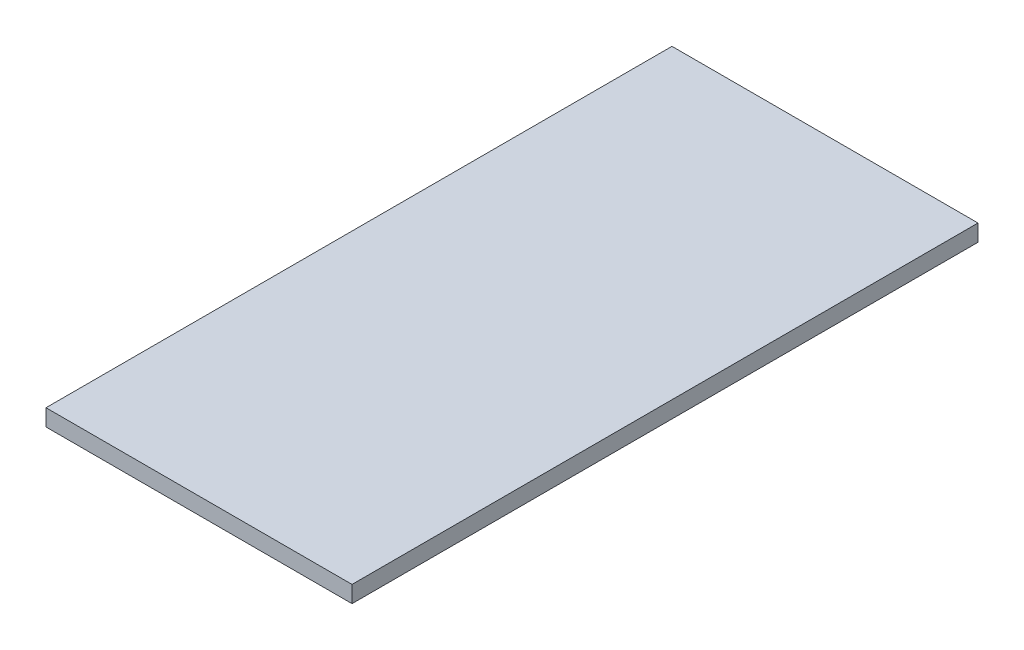
SolidWorks part; units mm, degrees
ref_plane "Front Plane" through (0, 0, 0) normal (0, 0, 1) x (1, 0, 0)
ref_plane "Top Plane" through (0, 0, 0) normal (0, 1, 0) x (1, 0, 0)
ref_plane "Right Plane" through (0, 0, 0) normal (1, 0, 0) x (0, 0, -1)
sketch "Sketch1" plane through (0, 0, 0) normal (0, 1, 0) x (1, 0, 0)
  line L1 (-11, 22.5) -> (11, 22.5)
  line L2 (-11, 22.5) -> (-11, -22.5)
  line L3 (-11, -22.5) -> (11, -22.5)
  line L4 (11, 22.5) -> (11, -22.5)
  line L5 (-11, 22.5) -> (11, -22.5) construction
  line L6 (-11, -22.5) -> (11, 22.5) construction
  point P0 (0, 0)
  dimension "D1" = 45
  dimension "D2" = 22
extrude "Boss-Extrude1" add sketch "Sketch1" along normal blind 1.2
